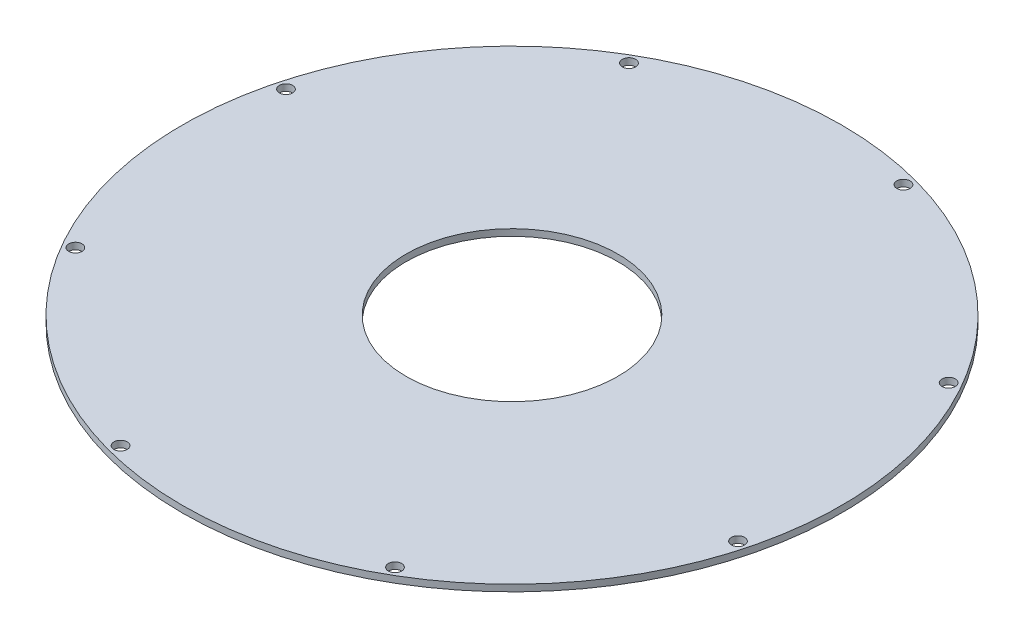
SolidWorks part; units mm, degrees
material "Thornel Mat VMA"
ref_plane "Front Plane" through (0, 0, 0) normal (0, 0, 1) x (1, 0, 0)
ref_plane "Top Plane" through (0, 0, 0) normal (0, 1, 0) x (1, 0, 0)
ref_plane "Right Plane" through (0, 0, 0) normal (1, 0, 0) x (0, 0, -1)
sketch "Sketch1" plane through (0, 0, 0) normal (0, 1, 0) x (1, 0, 0)
  circle A0 centre (0, 0) radius 32
  circle A1 centre (0, 0) radius 99.5
  dimension "D1" = 64
  dimension "D2" = 199
extrude "Base" add sketch "Sketch1" along normal mid plane 2
sketch "Sketch2" plane through (0, 1, 0) normal (0, 1, 0) x (1, 0, 0)
  line L0 (24.976, 93.2118) -> (25.7525, 96.1096) construction
  line L1 (24.976, 93.2118) -> (0, 0) construction
  line L2 (0, 0) -> (0, 99.5) construction
  circle A0 centre (24.976, 93.2118) radius 2
  circle A2 centre (0, 0) radius 99.5 construction
  dimension "D1" = 4
  dimension "D2" = 3
  dimension "D3" = 15
extrude "Structural Hole" cut sketch "Sketch2" against normal through all
pattern_circular "Structural Hole Pattern" count 8 over 360 about axis through (0, 0, 0) along (0, 1, 0) of "Structural Hole"
equation "\"lift_fan_diameter\"=64"
equation "\"D1@Sketch1\"=\"lift_fan_diameter\""
equation "\"outer_diameter\"=199"
equation "\"D2@Sketch1\"=\"outer_diameter\""
equation "\"bolt_diameter\"=4"
equation "\"D1@Sketch2\"=\"bolt_diameter\""
equation "\"wall_thickness\"=3"
equation "\"D2@Sketch2\"=\"wall_thickness\""
